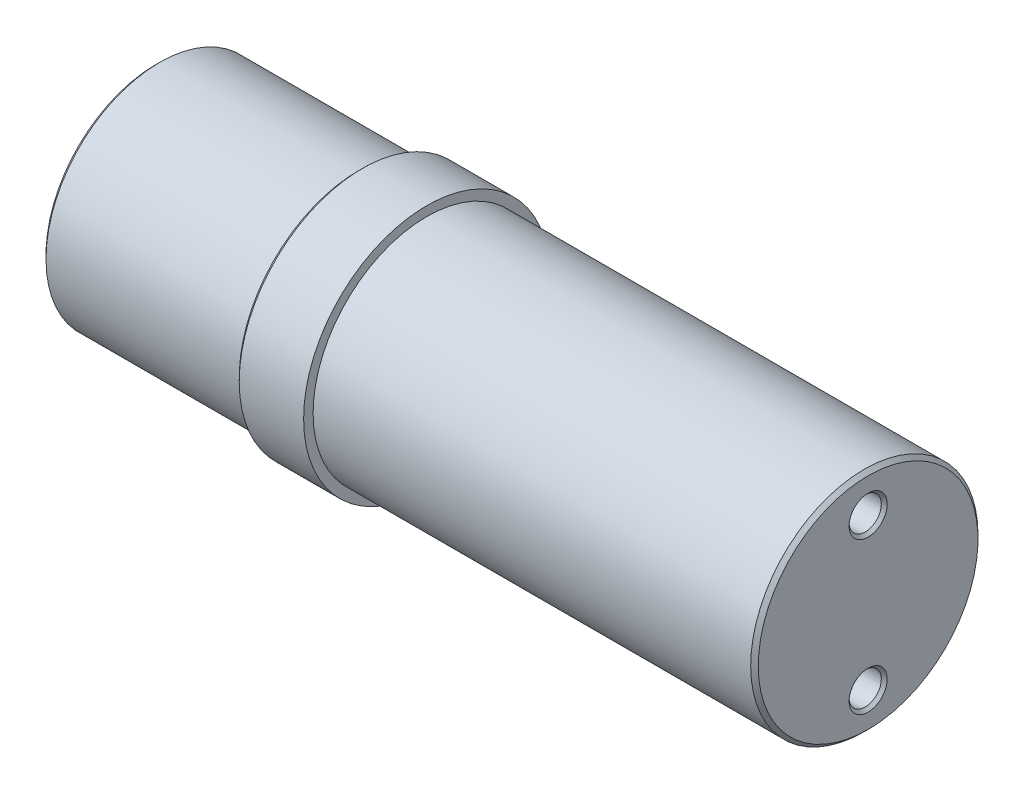
SolidWorks part; units mm, degrees
ref_plane "Front Plane" through (0, 0, 0) normal (0, 0, 1) x (1, 0, 0)
ref_plane "Top Plane" through (0, 0, 0) normal (0, 1, 0) x (1, 0, 0)
ref_plane "Right Plane" through (0, 0, 0) normal (1, 0, 0) x (0, 0, -1)
sketch "Sketch1" plane through (0, 0, 0) normal (0, 0, 1) x (1, 0, 0)
  line L0 (0, 0) -> (0, 30)
  line L1 (0, 30) -> (53.5, 30)
  line L2 (53.5, 30) -> (53.5, 32.5)
  line L3 (53.5, 32.5) -> (71.5, 32.5)
  line L4 (71.5, 32.5) -> (71.5, 30)
  line L5 (71.5, 30) -> (188, 30)
  line L6 (188, 30) -> (188, 0)
  line L7 (188, 0) -> (0, 0)
  line L8 (0, 0) -> (221.1804, 0) construction
  dimension "D1" = 188
  dimension "D2" = 60
  dimension "D3" = 65
  dimension "D4" = 60
  dimension "D5" = 53.5
  dimension "D6" = 18
revolve "Revolve1" add sketch "Sketch1" angle 360 about L8
sketch "Sketch2" plane through (0, 0, 0) normal (-1, 0, 0) x (0, 0, 1)
  line L0 (0, 20) -> (0, -20) construction
  circle A0 centre (0, 20) radius 5
  circle A2 centre (0, -20) radius 5
  point P4 (0, 0)
  dimension "D3" = 10
  dimension "D1" = 40
hole_wizard "M10 Tapped Hole1" positions "3DSketch1" profile "Sketch3" tap size "M10" standard "ISO"
sketch3d "3DSketch1"
  point P0 (0, 20, 0)
  point P3 (0, -20, 0)
sketch "Sketch3" plane through (0, 20, 0) normal (0, 1, 0) x (0, 0, 1)
  line L0 (0, 0) -> (0, 27.0537)
  line L1 (0, 27.0537) -> (4.25, 24.5)
  line L2 (4.25, 24.5) -> (4.25, 0.775)
  line L3 (4.25, 0.775) -> (5.025, 0)
  line L5 (5.025, 0) -> (0, 0)
  line L6 (-4.25, 0.775) -> (-5.025, 0) construction
  line L10 (0, 27.0537) -> (-4.25, 24.5) construction
  line L11 (0, -6.35) -> (0, 107.95) construction
  dimension "Tap Drill Dia." = 8.5
  dimension "Tap Drill Depth" = 24.5
  dimension "Near C'Sink Dia." = 10.05
  dimension "Near C'Sink Angle" = 90
  dimension "Drill Angle" = 118
cosmetic thread "Hole Thread1" parameters "D1"=20, "D2"=10
cosmetic thread "Hole Thread2" parameters "D1"=20, "D2"=10
sketch "Sketch4" plane through (188, 0, 0) normal (1, 0, 0) x (0, 0, -1)
  line L0 (0, -20) -> (0, 20)
  point P4 (0, 0)
hole_wizard "M10 Tapped Hole2" positions "3DSketch2" profile "Sketch5" tap size "M10" standard "ISO"
sketch3d "3DSketch2"
  point P0 (188, 20, 0)
  point P3 (188, -20, 0)
sketch "Sketch5" plane through (188, 20, 0) normal (0, 1, 0) x (0, 0, -1)
  line L0 (0, 0) -> (0, 27.0537)
  line L1 (0, 27.0537) -> (4.25, 24.5)
  line L2 (4.25, 24.5) -> (4.25, 0.775)
  line L3 (4.25, 0.775) -> (5.025, 0)
  line L5 (5.025, 0) -> (0, 0)
  line L6 (-4.25, 0.775) -> (-5.025, 0) construction
  line L10 (0, 27.0537) -> (-4.25, 24.5) construction
  line L11 (0, -6.35) -> (0, 107.95) construction
  dimension "Tap Drill Dia." = 8.5
  dimension "Tap Drill Depth" = 24.5
  dimension "Near C'Sink Dia." = 10.05
  dimension "Near C'Sink Angle" = 90
  dimension "Drill Angle" = 118
cosmetic thread "Hole Thread3" parameters "D1"=20, "D2"=10
cosmetic thread "Hole Thread4" parameters "D1"=20, "D2"=10
chamfer "Chamfer1" distance 1 angle 45 3 edges at (53.5, 0, 32.5) (188, 0, 30) (0, 0, 30)
